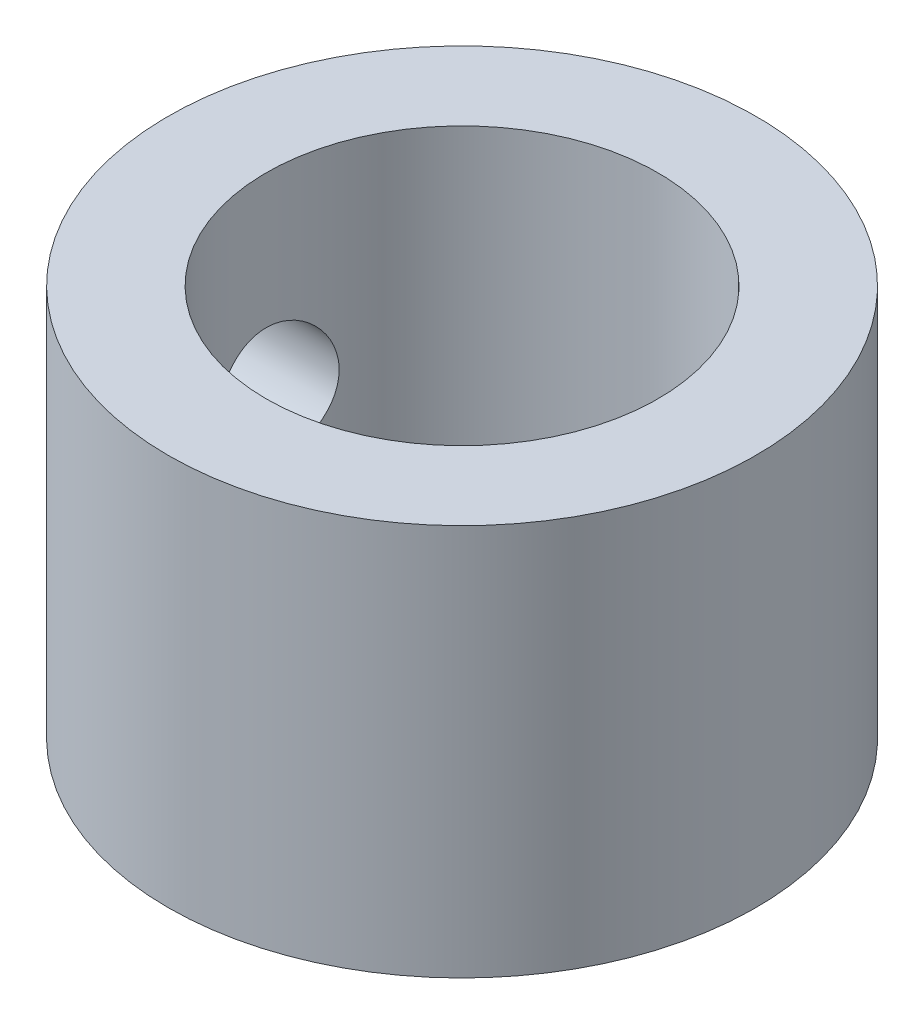
SolidWorks part; units mm, degrees
ref_plane "Front Plane" through (0, 0, 0) normal (0, 0, 1) x (1, 0, 0)
ref_plane "Top Plane" through (0, 0, 0) normal (0, 1, 0) x (1, 0, 0)
ref_plane "Right Plane" through (0, 0, 0) normal (1, 0, 0) x (0, 0, -1)
sketch "Sketch1" plane through (0, 0, 0) normal (0, 1, 0) x (1, 0, 0)
  circle A0 centre (0, 0) radius 9.525
  dimension "D1" = 19.05
extrude "Boss-Extrude1" add sketch "Sketch1" along normal blind 12.7
sketch "Sketch2" plane through (0, 12.7, 0) normal (0, 1, 0) x (1, 0, 0)
  circle A0 centre (0, 0) radius 6.35
  dimension "D1" = 12.7
extrude "Cut-Extrude1" cut sketch "Sketch2" against normal blind 9.525
sketch "Sketch3" plane through (0, 0, 0) normal (1, 0, 0) x (0, 0, -1)
  circle A0 centre (0, 6.3188) radius 2.032
  dimension "D1" = 4.064
extrude "Cut-Extrude2" cut sketch "Sketch3" against normal through all
sketch "Sketch4" plane through (0, 0, 0) normal (0, -1, 0) x (1, 0, 0)
  circle A0 centre (0, 0) radius 5.2387
  dimension "D1" = 10.4775
extrude "Cut-Extrude3" cut sketch "Sketch4" against normal through all
